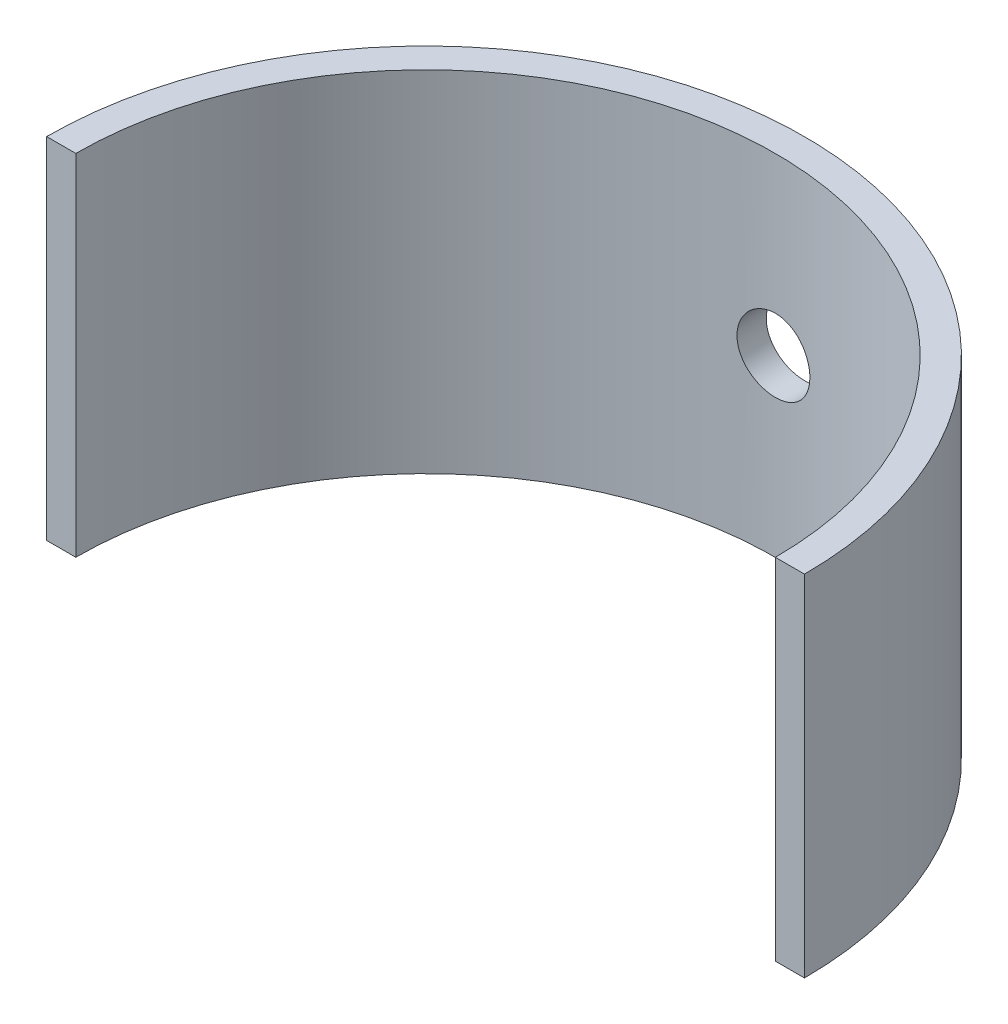
SolidWorks part; units mm, degrees
ref_plane "前视基准面" through (0, 0, 0) normal (0, 0, 1) x (1, 0, 0)
ref_plane "上视基准面" through (0, 0, 0) normal (0, 1, 0) x (1, 0, 0)
ref_plane "右视基准面" through (0, 0, 0) normal (1, 0, 0) x (0, 0, -1)
sketch "草图1" plane through (0, 0, 0) normal (0, 0, 1) x (1, 0, 0)
  line L0 (0, 25.248) -> (0, -19.6815) construction
  line L2 (24, 24) -> (26, 24)
  line L3 (24, 24) -> (24, 0)
  line L4 (24, 0) -> (26, 0)
  line L5 (26, 24) -> (26, 0)
  dimension "D1" = 24
  dimension "D2" = 26
  dimension "D3" = 24
revolve "旋转1" add sketch "草图1" angle 180 about L0
sketch "草图2" plane through (0, 0, 0) normal (0, 0, 1) x (1, 0, 0)
  line L0 (-2.7955, 12) -> (3.0422, 12) construction
  line L1 (0, 15.5355) -> (0, 8.6289) construction
  line L2 (26, 0) -> (26, 24) construction
  line L3 (-24, 0) -> (24, 0) construction
  circle A0 centre (0, 12) radius 2.5
  dimension "D1" = 5
  dimension "D2" = 26
  dimension "D3" = 12
extrude "切除-拉伸1" cut sketch "草图2" against normal through all
